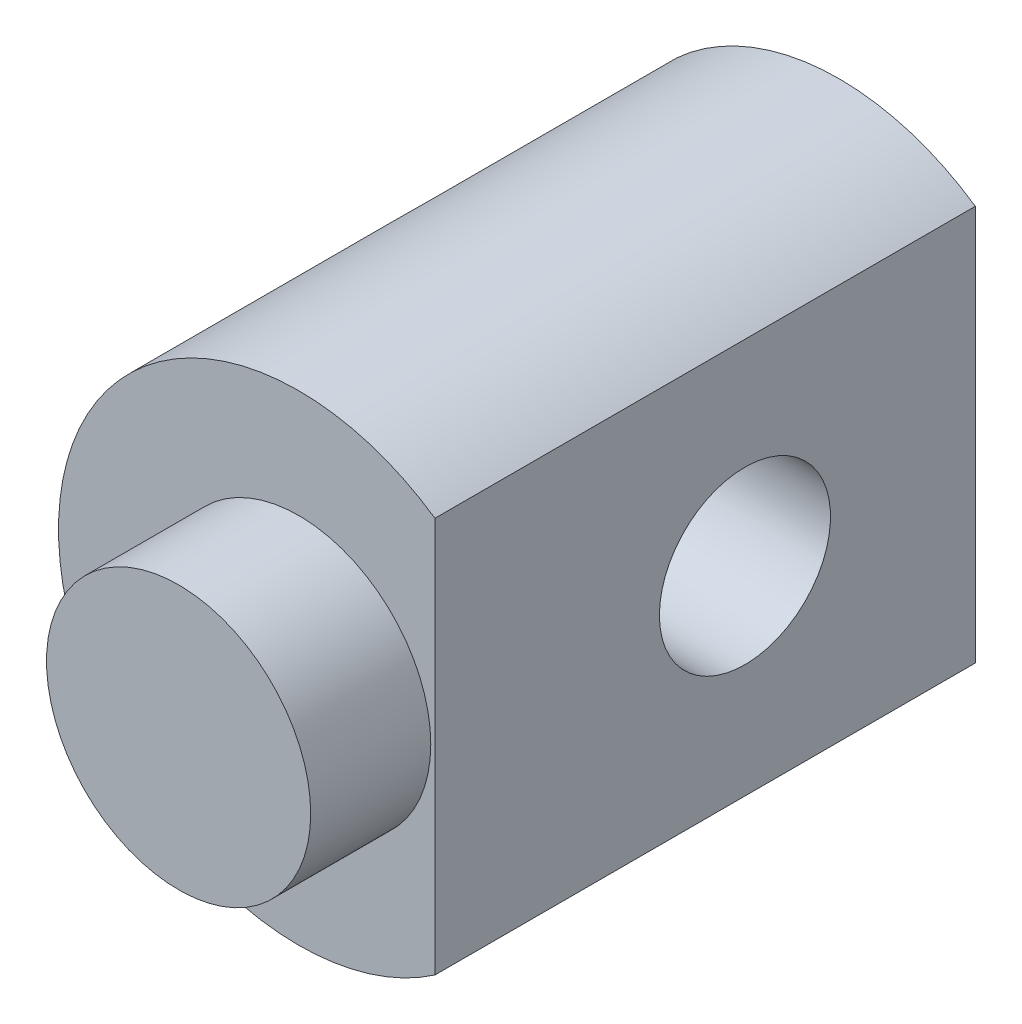
SolidWorks part; units mm, degrees
ref_plane "Front Plane" through (0, 0, 0) normal (0, 0, 1) x (1, 0, 0)
ref_plane "Top Plane" through (0, 0, 0) normal (0, 1, 0) x (1, 0, 0)
ref_plane "Right Plane" through (0, 0, 0) normal (1, 0, 0) x (0, 0, -1)
sketch "Sketch1" plane through (0, 0, 0) normal (0, 0, 1) x (1, 0, 0)
  circle A0 centre (0, 0) radius 11
  dimension "D1" = 22
extrude "Boss-Extrude1" add sketch "Sketch1" along normal blind 10
sketch "Sketch2" plane through (0, 0, 0) normal (0, 0, -1) x (-1, 0, 0)
  circle A0 centre (0, 0) radius 20
  dimension "D1" = 40
extrude "Boss-Extrude2" add sketch "Sketch2" along normal blind 45
sketch "Sketch3" plane through (0, 0, 0) normal (1, 0, 0) x (0, 0, -1)
  line L0 (25.4417, 14.75) -> (75.4417, 14.75)
  line L1 (25.4417, -14.5) -> (81.5553, -14.5)
  line L2 (75.4417, 14.75) -> (75.4417, -14.5)
  arc A0 (25.4417, 14.75) -> (25.4417, -14.5) centre (25.4417, 0.125) ccw
  dimension "D1" = 29.25
extrude "Cut-Extrude1" cut sketch "Sketch3" against normal through all contours L0 A0 L1 L2
sketch "Sketch5" plane through (0, 0, 0) normal (-1, 0, 0) x (0, 0, 1)
  line L0 (-10.8167, 0.125) -> (-25.8167, 0.125) construction
  arc A0 (-25.4417, -14.5) -> (-25.4417, 14.75) centre (-25.4417, 0.125) ccw construction
  circle A1 centre (-25.8167, 0.125) radius 7.125
  dimension "D2" = 14.25
  dimension "D1" = 15
extrude "Cut-Extrude2" cut sketch "Sketch5" against normal through all
sketch "Sketch6" plane through (0, 0, -45) normal (0, 0, -1) x (-1, 0, 0)
  line L0 (-11.3464, 16.47) -> (-11.3464, -16.47)
  arc A0 (-11.3464, 16.47) -> (-11.3464, -16.47) centre (0, 0) ccw
extrude "Cut-Extrude3" cut sketch "Sketch6" against normal up to surface (45 mm away) up to face at (11, 0, 0)
